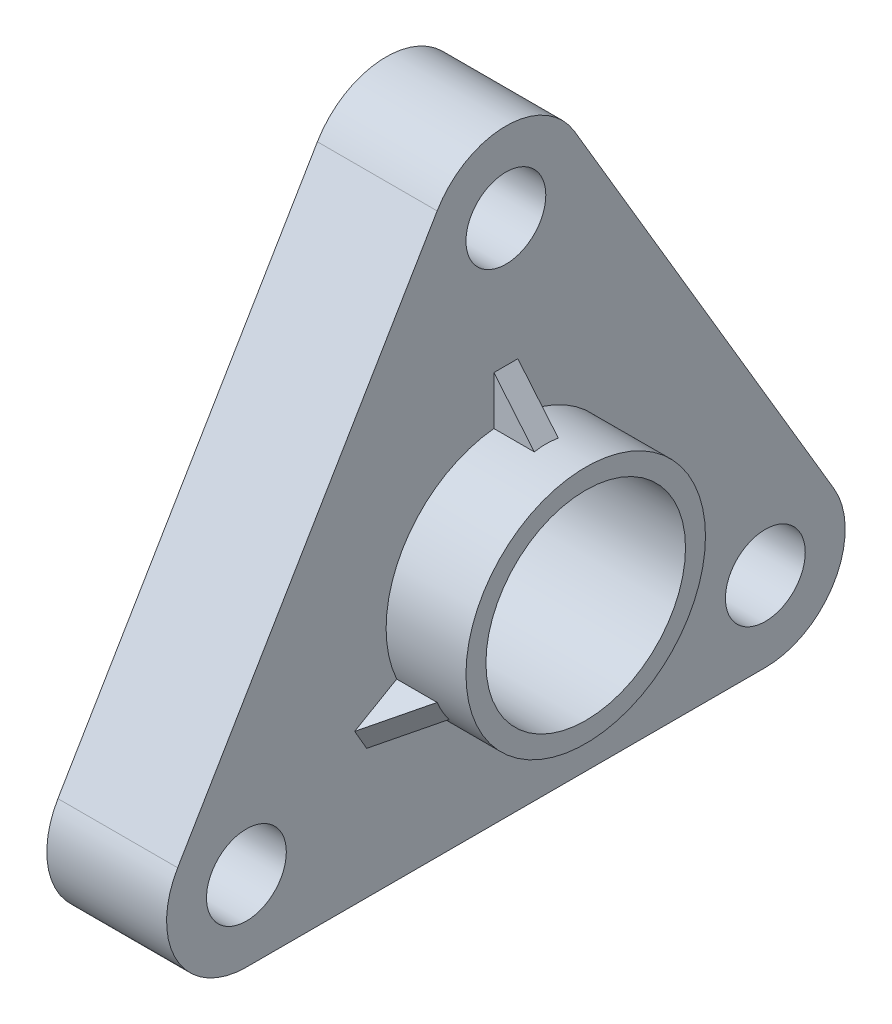
SolidWorks part; units mm, degrees
ref_plane "Front Plane" through (0, 0, 0) normal (0, 0, 1) x (1, 0, 0)
ref_plane "Top Plane" through (0, 0, 0) normal (0, 1, 0) x (1, 0, 0)
ref_plane "Right Plane" through (0, 0, 0) normal (1, 0, 0) x (0, 0, -1)
sketch "Sketch1" plane through (0, 0, 0) normal (1, 0, 0) x (0, 0, -1)
  line L0 (0, 0) -> (0, 8.8185) construction
  line L1 (-41.1093, -12.9127) -> (-8.6093, 42.0873)
  line L2 (41.1093, -12.9127) -> (8.6093, 42.0873)
  line L3 (-32.5, -28) -> (32.5, -28)
  circle A0 centre (0, 0) radius 12.5
  arc A1 (8.6093, 42.0873) -> (-8.6093, 42.0873) centre (0, 37) ccw
  arc A2 (32.5, -28) -> (41.1093, -12.9127) centre (32.5, -18) ccw
  arc A3 (-41.1093, -12.9127) -> (-32.5, -28) centre (-32.5, -18) ccw
  circle A4 centre (0, 37) radius 5
  circle A5 centre (32.5, -18) radius 5
  circle A6 centre (-32.5, -18) radius 5
  dimension "D1" = 20
  dimension "D2" = 25
  dimension "D6" = 10
  dimension "D3" = 65
  dimension "D4" = 18
  dimension "D5" = 55
extrude "Boss-Extrude1" add sketch "Sketch1" along normal blind 15
sketch "Sketch2" plane through (15, 0, 0) normal (1, 0, 0) x (0, 0, -1)
  circle A0 centre (0, 0) radius 12.5 construction
  circle A1 centre (0, 0) radius 12.5
  circle A2 centre (0, 0) radius 15
  dimension "D1" = 30
extrude "Boss-Extrude2" add sketch "Sketch2" along normal blind 10
sketch "Sketch3" plane through (0, 0, 0) normal (0, 0, 1) x (1, 0, 0)
  line L0 (20, 15) -> (15, 21)
  line L1 (25, 15) -> (15, 15) construction
  line L2 (15, 42.0873) -> (15, -12.9127) construction
  dimension "D1" = 6
rib "Rib1" sketch "Sketch3" sketch "Sketch3" thickness 3 extrusion direction parallel to sketch draft on no parameters "D1"=3
pattern_circular "CirPattern1" count 3 over 360 about axis through (0, 0, 0) along (1, 0, 0) of "Rib1"
